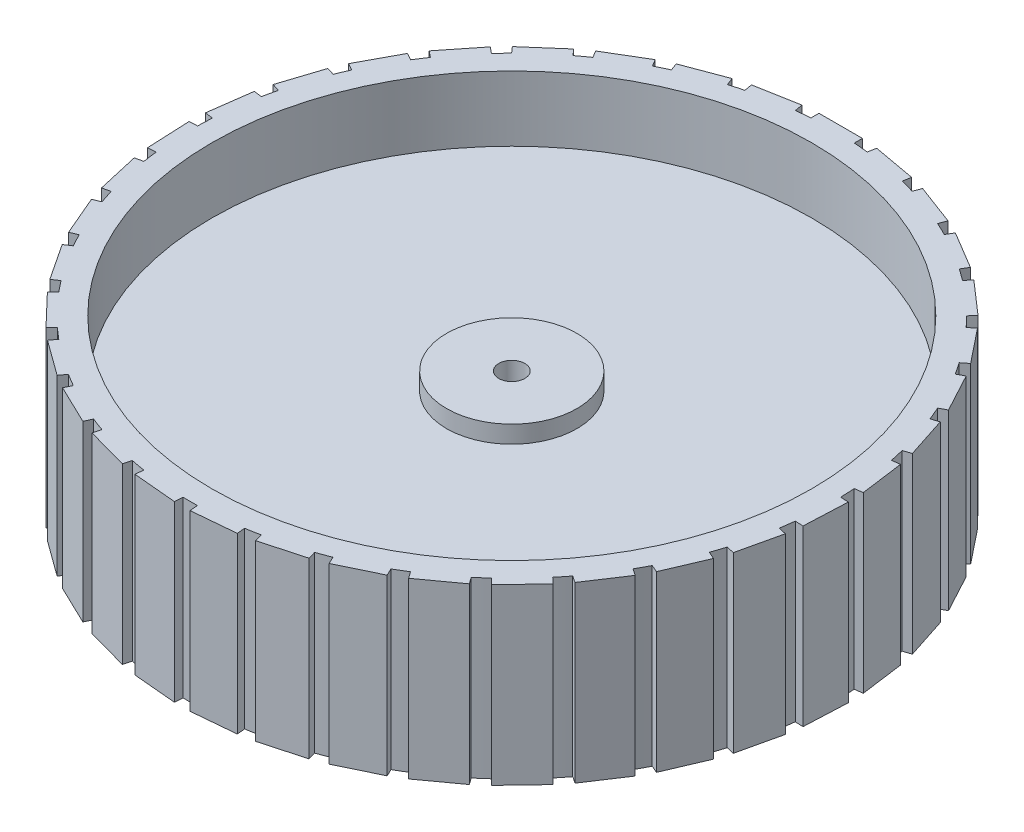
SolidWorks part; units mm, degrees
ref_plane "Front Plane" through (0, 0, 0) normal (0, 0, 1) x (1, 0, 0)
ref_plane "Top Plane" through (0, 0, 0) normal (0, 1, 0) x (1, 0, 0)
ref_plane "Right Plane" through (0, 0, 0) normal (1, 0, 0) x (0, 0, -1)
sketch "Sketch1" plane through (0, 0, 0) normal (0, 1, 0) x (1, 0, 0)
  circle A1 centre (0, 0) radius 34.5
  dimension "D2" = 69
extrude "Boss-Extrude2" add sketch "Sketch1" along normal mid plane 5
sketch "Sketch3" plane through (0, 2.5, 0) normal (0, 1, 0) x (1, 0, 0)
  circle A0 centre (0, 0) radius 7.5
  dimension "D1" = 15
extrude "Boss-Extrude4" add sketch "Sketch3" along normal blind 2
sketch "Sketch4" plane through (0, -2.5, 0) normal (0, -1, 0) x (1, 0, 0)
  circle A0 centre (0, 0) radius 5
  dimension "D1" = 10
extrude "Boss-Extrude5" add sketch "Sketch4" along normal blind 15
sketch "Sketch6" plane through (0, 4.5, 0) normal (0, 1, 0) x (1, 0, 0)
  circle A0 centre (0, 0) radius 1.5
  dimension "D1" = 3
extrude "Cut-Extrude1" cut sketch "Sketch6" against normal through all
sketch "Sketch7" plane through (0, 0, 0) normal (0, 0, 1) x (1, 0, 0)
  line L0 (-34.5, -2.5) -> (34.5, -2.5) construction
  circle A0 centre (0, -10.5) radius 1.5
  dimension "D1" = 3
  dimension "D2" = 8
extrude "Cut-Extrude3" cut sketch "Sketch7" against normal mid plane 15
sketch "Sketch9" plane through (0, 0, 0) normal (0, 1, 0) x (1, 0, 0)
  circle A0 centre (0, 0) radius 37
  circle A1 centre (0, 0) radius 34.5
  dimension "D1" = 74
  dimension "D2" = 69
extrude "Boss-Extrude7" add sketch "Sketch9" along normal mid plane 20
sketch "Sketch10" plane through (0, 10, 0) normal (0, 1, 0) x (1, 0, 0)
  line L0 (2.4972, 37.848) -> (-2.5028, 37.848)
  line L1 (-2.5028, 37.848) -> (-2.5028, 36.848)
  line L2 (2.4972, 37.848) -> (2.4972, 36.848)
  line L3 (9.2151, 36.7939) -> (4.2954, 37.6867)
  line L4 (4.2954, 37.6867) -> (4.1169, 36.7028)
  line L5 (9.2151, 36.7939) -> (9.0365, 35.81)
  line L6 (15.6368, 34.5572) -> (10.9556, 36.3141)
  line L7 (10.9556, 36.3141) -> (10.6043, 35.3778)
  line L8 (15.6368, 34.5572) -> (15.2854, 33.621)
  line L9 (21.5559, 31.2098) -> (17.2637, 33.7743)
  line L10 (17.2637, 33.7743) -> (16.7508, 32.9158)
  line L11 (21.5559, 31.2098) -> (21.043, 30.3513)
  line L12 (26.7823, 26.8593) -> (23.0169, 30.149)
  line L13 (23.0169, 30.149) -> (22.359, 29.3959)
  line L14 (26.7823, 26.8593) -> (26.1243, 26.1062)
  line L15 (31.1478, 21.6455) -> (28.0303, 25.5546)
  line L16 (28.0303, 25.5546) -> (27.2485, 24.9311)
  line L17 (31.1478, 21.6455) -> (30.3659, 21.022)
  line L18 (34.5122, 15.736) -> (32.1428, 20.139)
  line L19 (32.1428, 20.139) -> (31.2622, 19.6651)
  line L20 (34.5122, 15.736) -> (33.6316, 15.2621)
  line L21 (36.7673, 9.3207) -> (35.2222, 14.076)
  line L22 (35.2222, 14.076) -> (34.2712, 13.767)
  line L23 (36.7673, 9.3207) -> (35.8162, 9.0117)
  line L24 (37.8407, 2.6059) -> (37.1695, 7.5606)
  line L25 (37.1695, 7.5606) -> (36.1786, 7.4264)
  line L26 (37.8407, 2.6059) -> (36.8498, 2.4716)
  line L27 (37.6979, -4.1927) -> (37.9222, 0.8022)
  line L28 (37.9222, 0.8022) -> (36.9232, 0.8471)
  line L29 (37.6979, -4.1927) -> (36.6989, -4.1479)
  line L30 (36.3434, -10.8566) -> (37.456, -5.9819)
  line L31 (37.456, -5.9819) -> (36.4811, -5.7594)
  line L32 (36.3434, -10.8566) -> (35.3685, -10.634)
  line L33 (33.8209, -17.1715) -> (35.786, -12.5738)
  line L34 (35.786, -12.5738) -> (34.8665, -12.1808)
  line L35 (33.8209, -17.1715) -> (32.9013, -16.7784)
  line L36 (30.2113, -22.9345) -> (32.9657, -18.7616)
  line L37 (32.9657, -18.7616) -> (32.1312, -18.2107)
  line L38 (30.2113, -22.9345) -> (29.3767, -22.3836)
  line L39 (25.6306, -27.9603) -> (29.086, -24.3464)
  line L40 (29.086, -24.3464) -> (28.3632, -23.6553)
  line L41 (25.6306, -27.9603) -> (24.9079, -27.2693)
  line L42 (20.2262, -32.0875) -> (24.2713, -29.1486)
  line L43 (24.2713, -29.1486) -> (23.6835, -28.3396)
  line L44 (20.2262, -32.0875) -> (19.6385, -31.2785)
  line L45 (14.1718, -35.1834) -> (18.6766, -33.014)
  line L46 (18.6766, -33.014) -> (18.2427, -32.113)
  line L47 (14.1718, -35.1834) -> (13.7379, -34.2824)
  line L48 (7.6618, -37.1485) -> (12.4816, -35.8183)
  line L49 (12.4816, -35.8183) -> (12.2155, -34.8543)
  line L50 (7.6618, -37.1485) -> (7.3957, -36.1845)
  line L51 (0.9055, -37.9195) -> (5.8854, -37.4713)
  line L52 (5.8854, -37.4713) -> (5.7958, -36.4754)
  line L53 (0.9055, -37.9195) -> (0.8159, -36.9235)
  line L54 (-5.8798, -37.4718) -> (-0.8999, -37.92)
  line L55 (-0.8999, -37.92) -> (-0.8103, -36.924)
  line L56 (-5.8798, -37.4718) -> (-5.7902, -36.4759)
  line L57 (-12.4762, -35.8198) -> (-7.6564, -37.1499)
  line L58 (-7.6564, -37.1499) -> (-7.3903, -36.186)
  line L59 (-12.4762, -35.8198) -> (-12.2101, -34.8558)
  line L60 (-18.6715, -33.0164) -> (-14.1667, -35.1858)
  line L61 (-14.1667, -35.1858) -> (-13.7328, -34.2849)
  line L62 (-18.6715, -33.0164) -> (-18.2377, -32.1154)
  line L63 (-24.2668, -29.1519) -> (-20.2217, -32.0908)
  line L64 (-20.2217, -32.0908) -> (-19.6339, -31.2818)
  line L65 (-24.2668, -29.1519) -> (-23.679, -28.3429)
  line L66 (-29.0821, -24.3504) -> (-25.6268, -27.9644)
  line L67 (-25.6268, -27.9644) -> (-24.904, -27.2733)
  line L68 (-29.0821, -24.3504) -> (-28.3593, -23.6593)
  line L69 (-32.9627, -18.7663) -> (-30.2082, -22.9391)
  line L70 (-30.2082, -22.9391) -> (-29.3736, -22.3882)
  line L71 (-32.9627, -18.7663) -> (-32.1281, -18.2154)
  line L72 (-35.7838, -12.579) -> (-33.8187, -17.1766)
  line L73 (-33.8187, -17.1766) -> (-32.8991, -16.7836)
  line L74 (-35.7838, -12.579) -> (-34.8643, -12.186)
  line L75 (-37.4548, -5.9874) -> (-36.3422, -10.862)
  line L76 (-36.3422, -10.862) -> (-35.3673, -10.6395)
  line L77 (-37.4548, -5.9874) -> (-36.4799, -5.7649)
  line L78 (-37.922, 0.7966) -> (-37.6976, -4.1983)
  line L79 (-37.6976, -4.1983) -> (-36.6986, -4.1535)
  line L80 (-37.922, 0.7966) -> (-36.923, 0.8415)
  line L81 (-37.1703, 7.5551) -> (-37.8415, 2.6003)
  line L82 (-37.8415, 2.6003) -> (-36.8505, 2.4661)
  line L83 (-37.1703, 7.5551) -> (-36.1793, 7.4208)
  line L84 (-35.2239, 14.0707) -> (-36.769, 9.3154)
  line L85 (-36.769, 9.3154) -> (-35.818, 9.0064)
  line L86 (-35.2239, 14.0707) -> (-34.2729, 13.7616)
  line L87 (-32.1455, 20.134) -> (-34.5148, 15.731)
  line L88 (-34.5148, 15.731) -> (-33.6342, 15.2572)
  line L89 (-32.1455, 20.134) -> (-31.2649, 19.6602)
  line L90 (-28.0338, 25.5503) -> (-31.1513, 21.6411)
  line L91 (-31.1513, 21.6411) -> (-30.3694, 21.0176)
  line L92 (-28.0338, 25.5503) -> (-27.252, 24.9268)
  line L93 (-23.0211, 30.1453) -> (-26.7865, 26.8556)
  line L94 (-26.7865, 26.8556) -> (-26.1285, 26.1025)
  line L95 (-23.0211, 30.1453) -> (-22.3632, 29.3922)
  line L96 (-17.2685, 33.7714) -> (-21.5608, 31.2069)
  line L97 (-21.5608, 31.2069) -> (-21.0479, 30.3485)
  line L98 (-17.2685, 33.7714) -> (-16.7556, 32.913)
  line L99 (-10.9609, 36.3121) -> (-15.6421, 34.5552)
  line L100 (-15.6421, 34.5552) -> (-15.2907, 33.619)
  line L101 (-10.9609, 36.3121) -> (-10.6095, 35.3759)
  line L102 (-4.301, 37.6857) -> (-9.2206, 36.7929)
  line L103 (-9.2206, 36.7929) -> (-9.0421, 35.809)
  line L104 (-4.301, 37.6857) -> (-4.1224, 36.7018)
  circle A0 centre (0, 0) radius 37 construction
  spline S0 degree 2 poles (-2.5028, 36.848) (-1.251, 36.9168) (0, 37) knots 0 0 0 1 1 1
  spline S1 degree 2 poles (2.4972, 36.848) (1.25, 36.9464) (0, 37) knots 0 0 0 1 1 1
  spline S2 degree 2 poles (4.1169, 36.7028) (5.3609, 36.5469) (6.6066, 36.4054) knots 0 0 0 1 1 1
  spline S3 degree 2 poles (9.0365, 35.81) (7.827, 36.1295) (6.6066, 36.4054) knots 0 0 0 1 1 1
  spline S4 degree 2 poles (10.6043, 35.3778) (11.8004, 35.0024) (13.0009, 34.6407) knots 0 0 0 1 1 1
  spline S5 degree 2 poles (15.2854, 33.621) (14.1524, 34.1513) (13.0009, 34.6407) knots 0 0 0 1 1 1
  spline S6 degree 2 poles (16.7508, 32.9158) (17.8607, 32.3328) (18.9773, 31.7626) knots 0 0 0 1 1 1
  spline S7 degree 2 poles (21.043, 30.3513) (20.0229, 31.0755) (18.9773, 31.7626) knots 0 0 0 1 1 1
  spline S8 degree 2 poles (22.359, 29.3959) (23.3469, 28.6241) (24.3437, 27.8636) knots 0 0 0 1 1 1
  spline S9 degree 2 poles (26.1243, 26.1062) (25.2498, 27.0009) (24.3437, 27.8636) knots 0 0 0 1 1 1
  spline S10 degree 2 poles (27.2485, 24.9311) (28.0828, 23.9953) (28.9278, 23.0691) knots 0 0 0 1 1 1
  spline S11 degree 2 poles (30.3659, 21.022) (29.6653, 22.0584) (28.9278, 23.0691) knots 0 0 0 1 1 1
  spline S12 degree 2 poles (31.2622, 19.6651) (31.916, 18.5953) (32.582, 17.5331) knots 0 0 0 1 1 1
  spline S13 degree 2 poles (33.6316, 15.2621) (33.1272, 16.407) (32.582, 17.5331) knots 0 0 0 1 1 1
  spline S14 degree 2 poles (34.2712, 13.767) (34.7234, 12.5977) (35.1891, 11.4336) knots 0 0 0 1 1 1
  spline S15 degree 2 poles (35.8162, 9.0117) (35.5244, 10.2282) (35.1891, 11.4336) knots 0 0 0 1 1 1
  spline S16 degree 2 poles (36.1786, 7.4264) (36.4148, 6.1951) (36.6651, 4.9666) knots 0 0 0 1 1 1
  spline S17 degree 2 poles (36.8498, 2.4716) (36.7799, 3.7207) (36.6651, 4.9666) knots 0 0 0 1 1 1
  spline S18 degree 2 poles (36.9232, 0.8471) (36.9358, -0.4066) (36.9627, -1.66) knots 0 0 0 1 1 1
  spline S19 degree 2 poles (36.6989, -4.1479) (36.8532, -2.9064) (36.9627, -1.66) knots 0 0 0 1 1 1
  spline S20 degree 2 poles (36.4811, -5.7594) (36.2696, -6.9952) (36.0723, -8.2333) knots 0 0 0 1 1 1
  spline S21 degree 2 poles (35.3685, -10.634) (35.742, -9.44) (36.0723, -8.2333) knots 0 0 0 1 1 1
  spline S22 degree 2 poles (34.8665, -12.1808) (34.4377, -13.3589) (34.0225, -14.5419) knots 0 0 0 1 1 1
  spline S23 degree 2 poles (32.9013, -16.7784) (33.482, -15.6703) (34.0225, -14.5419) knots 0 0 0 1 1 1
  spline S24 degree 2 poles (32.1312, -18.2107) (31.4989, -19.2933) (30.8792, -20.3832) knots 0 0 0 1 1 1
  spline S25 degree 2 poles (29.3767, -22.3836) (30.1459, -21.3969) (30.8792, -20.3832) knots 0 0 0 1 1 1
  spline S26 degree 2 poles (28.3632, -23.6553) (27.5478, -24.6076) (26.7434, -25.5693) knots 0 0 0 1 1 1
  spline S27 degree 2 poles (24.9079, -27.2693) (25.8409, -26.4358) (26.7434, -25.5693) knots 0 0 0 1 1 1
  spline S28 degree 2 poles (23.6835, -28.3396) (22.7112, -29.131) (21.7481, -29.9336) knots 0 0 0 1 1 1
  spline S29 degree 2 poles (19.6385, -31.2785) (20.7053, -30.625) (21.7481, -29.9336) knots 0 0 0 1 1 1
  spline S30 degree 2 poles (18.2427, -32.113) (17.1447, -32.7181) (16.0537, -33.3358) knots 0 0 0 1 1 1
  spline S31 degree 2 poles (13.7379, -34.2824) (14.9042, -33.83) (16.0537, -33.3358) knots 0 0 0 1 1 1
  spline S32 degree 2 poles (12.2155, -34.8543) (11.0271, -35.2536) (9.8434, -35.6666) knots 0 0 0 1 1 1
  spline S33 degree 2 poles (7.3957, -36.1845) (8.6241, -35.9476) (9.8434, -35.6666) knots 0 0 0 1 1 1
  spline S34 degree 2 poles (5.7958, -36.4754) (4.5551, -36.6561) (3.3167, -36.851) knots 0 0 0 1 1 1
  spline S35 degree 2 poles (0.8159, -36.9235) (2.0669, -36.9098) (3.3167, -36.851) knots 0 0 0 1 1 1
  spline S36 degree 2 poles (-0.8103, -36.924) (-2.0633, -36.8803) (-3.3167, -36.851) knots 0 0 0 1 1 1
  spline S37 degree 2 poles (-5.7902, -36.4759) (-4.5568, -36.6857) (-3.3167, -36.851) knots 0 0 0 1 1 1
  spline S38 degree 2 poles (-7.3903, -36.186) (-8.6153, -35.9193) (-9.8434, -35.6666) knots 0 0 0 1 1 1
  spline S39 degree 2 poles (-12.2101, -34.8558) (-11.0341, -35.2825) (-9.8434, -35.6666) knots 0 0 0 1 1 1
  spline S40 degree 2 poles (-13.7328, -34.2849) (-14.8905, -33.8037) (-16.0537, -33.3358) knots 0 0 0 1 1 1
  spline S41 degree 2 poles (-18.2377, -32.1154) (-17.1567, -32.7452) (-16.0537, -33.3358) knots 0 0 0 1 1 1
  spline S42 degree 2 poles (-19.6339, -31.2818) (-20.6871, -30.6016) (-21.7481, -29.9336) knots 0 0 0 1 1 1
  spline S43 degree 2 poles (-23.679, -28.3429) (-22.7279, -29.1556) (-21.7481, -29.9336) knots 0 0 0 1 1 1
  spline S44 degree 2 poles (-24.904, -27.2733) (-25.8188, -26.416) (-26.7434, -25.5693) knots 0 0 0 1 1 1
  spline S45 degree 2 poles (-28.3593, -23.6593) (-27.5685, -24.6288) (-26.7434, -25.5693) knots 0 0 0 1 1 1
  spline S46 degree 2 poles (-29.3736, -22.3882) (-30.1206, -21.3814) (-30.8792, -20.3832) knots 0 0 0 1 1 1
  spline S47 degree 2 poles (-32.1281, -18.2154) (-31.5231, -19.3105) (-30.8792, -20.3832) knots 0 0 0 1 1 1
  spline S48 degree 2 poles (-32.8991, -16.7836) (-33.4544, -15.6595) (-34.0225, -14.5419) knots 0 0 0 1 1 1
  spline S49 degree 2 poles (-34.8643, -12.186) (-34.4646, -13.3715) (-34.0225, -14.5419) knots 0 0 0 1 1 1
  spline S50 degree 2 poles (-35.3673, -10.6395) (-35.7129, -9.4344) (-36.0723, -8.2333) knots 0 0 0 1 1 1
  spline S51 degree 2 poles (-36.4799, -5.7649) (-36.2983, -7.0027) (-36.0723, -8.2333) knots 0 0 0 1 1 1
  spline S52 degree 2 poles (-36.6986, -4.1535) (-36.8235, -2.906) (-36.9627, -1.66) knots 0 0 0 1 1 1
  spline S53 degree 2 poles (-36.923, 0.8415) (-36.9653, -0.4088) (-36.9627, -1.66) knots 0 0 0 1 1 1
  spline S54 degree 2 poles (-36.8505, 2.4661) (-36.7506, 3.7158) (-36.6651, 4.9666) knots 0 0 0 1 1 1
  spline S55 degree 2 poles (-36.1793, 7.4208) (-36.4443, 6.1981) (-36.6651, 4.9666) knots 0 0 0 1 1 1
  spline S56 degree 2 poles (-35.818, 9.0064) (-35.4966, 10.2182) (-35.1891, 11.4336) knots 0 0 0 1 1 1
  spline S57 degree 2 poles (-34.2729, 13.7616) (-34.7519, 12.6059) (-35.1891, 11.4336) knots 0 0 0 1 1 1
  spline S58 degree 2 poles (-33.6342, 15.2572) (-33.1016, 16.3921) (-32.582, 17.5331) knots 0 0 0 1 1 1
  spline S59 degree 2 poles (-31.2649, 19.6602) (-31.9425, 18.6085) (-32.582, 17.5331) knots 0 0 0 1 1 1
  spline S60 degree 2 poles (-30.3694, 21.0176) (-29.6427, 22.0392) (-28.9278, 23.0691) knots 0 0 0 1 1 1
  spline S61 degree 2 poles (-27.252, 24.9268) (-28.1065, 24.013) (-28.9278, 23.0691) knots 0 0 0 1 1 1
  spline S62 degree 2 poles (-26.1285, 26.1025) (-25.2311, 26.9779) (-24.3437, 27.8636) knots 0 0 0 1 1 1
  spline S63 degree 2 poles (-22.3632, 29.3922) (-23.3671, 28.6457) (-24.3437, 27.8636) knots 0 0 0 1 1 1
  spline S64 degree 2 poles (-21.0479, 30.3485) (-20.0085, 31.0496) (-18.9773, 31.7626) knots 0 0 0 1 1 1
  spline S65 degree 2 poles (-16.7556, 32.913) (-17.8767, 32.3578) (-18.9773, 31.7626) knots 0 0 0 1 1 1
  spline S66 degree 2 poles (-15.2907, 33.619) (-14.1428, 34.1233) (-13.0009, 34.6407) knots 0 0 0 1 1 1
  spline S67 degree 2 poles (-10.6095, 35.3759) (-11.8117, 35.0298) (-13.0009, 34.6407) knots 0 0 0 1 1 1
  spline S68 degree 2 poles (-9.0421, 35.809) (-7.8226, 36.1002) (-6.6066, 36.4054) knots 0 0 0 1 1 1
  spline S69 degree 2 poles (-4.1224, 36.7018) (-5.3671, 36.5759) (-6.6066, 36.4054) knots 0 0 0 1 1 1
  point P3 (-0.0028, 37.848)
  dimension "D1" = 5
  dimension "D2" = 1
  dimension "D3" = 1
  dimension "D4" = 35
extrude "Boss-Extrude9" add sketch "Sketch10" against normal blind 20
